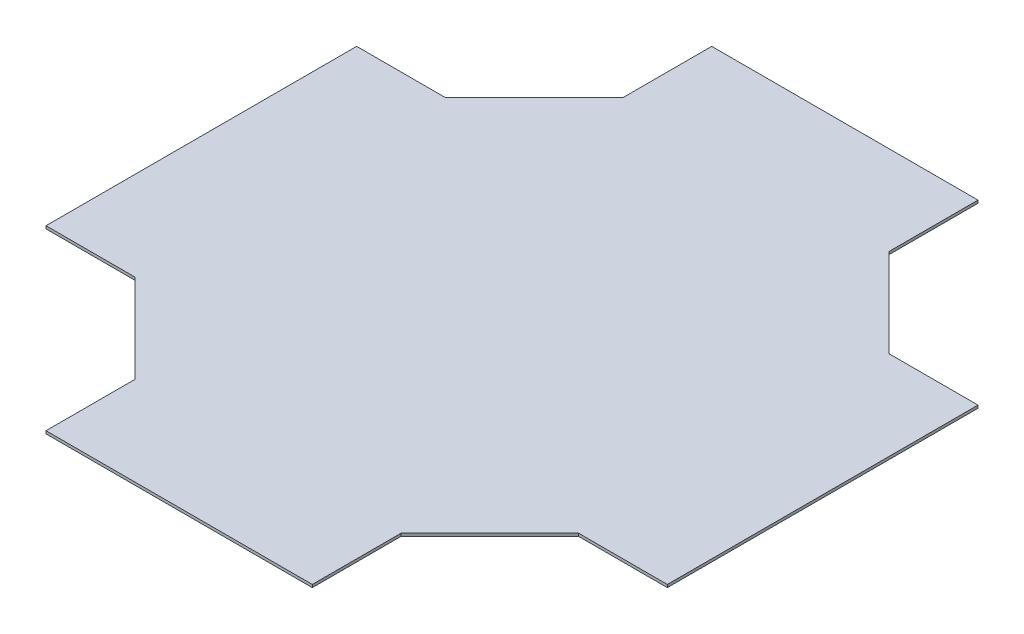
SolidWorks part; units mm, degrees
ref_plane "Front Plane" through (0, 0, 0) normal (0, 0, 1) x (1, 0, 0)
ref_plane "Top Plane" through (0, 0, 0) normal (0, 1, 0) x (1, 0, 0)
ref_plane "Right Plane" through (0, 0, 0) normal (1, 0, 0) x (0, 0, -1)
sketch "Sketch1" plane through (0, 0, 0) normal (0, 1, 0) x (1, 0, 0)
  line L0 (254, 177.8) -> (152.4, 279.4)
  line L1 (-355.6, 177.8) -> (355.6, 177.8)
  line L2 (-355.6, 177.8) -> (-355.6, -177.8)
  line L3 (-355.6, -177.8) -> (355.6, -177.8)
  line L4 (355.6, 177.8) -> (355.6, -177.8)
  line L5 (-355.6, 177.8) -> (355.6, -177.8) construction
  line L6 (-355.6, -177.8) -> (355.6, 177.8) construction
  line L7 (152.4, -381) -> (-152.4, -381)
  line L8 (152.4, -381) -> (152.4, 381)
  line L9 (152.4, 381) -> (-152.4, 381)
  line L10 (-152.4, -381) -> (-152.4, 381)
  line L11 (152.4, -381) -> (-152.4, 381) construction
  line L12 (152.4, 381) -> (-152.4, -381) construction
  line L13 (254, -177.8) -> (152.4, -279.4)
  line L14 (-152.4, 279.4) -> (-254, 177.8)
  line L15 (-254, -177.8) -> (-152.4, -279.4)
  point P0 (0, 0)
  point P6 (0, 0)
  point P19 (0, 0)
  point P20 (0, 0)
  point P21 (0, 0)
  point P22 (0, 0)
  dimension "D1" = 355.6
  dimension "D2" = 711.2
  dimension "D3" = 304.8
  dimension "D4" = 762
  dimension "D5" = 101.6
  dimension "D6" = 101.6
  dimension "D7" = 101.6
  dimension "D8" = 101.6
extrude "Boss-Extrude1" add sketch "Sketch1" along normal mid plane 3.175 contours L3 L10 L1 L2 | L10 L3 L8 L1 | L10 L1 L8 L9 | L10 L7 L8 L3 | L8 L3 L4 L1 | L8 L1 L0 | L13 L3 L8 | L3 L15 L10 | L10 L14 L1
